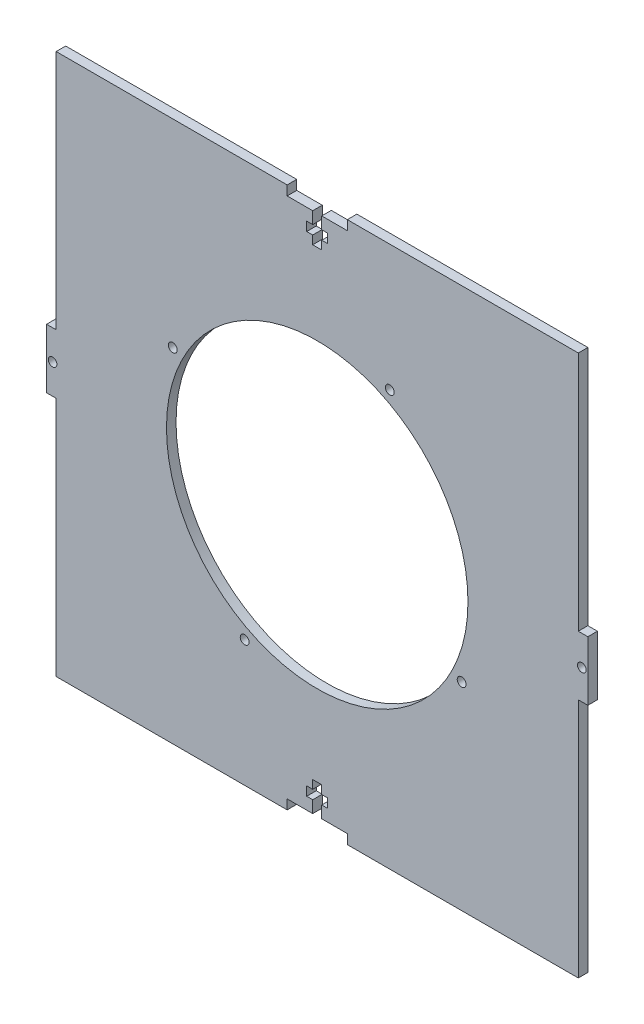
SolidWorks part; units mm, degrees
ref_plane "Front Plane" through (0, 0, 0) normal (0, 0, 1) x (1, 0, 0)
ref_plane "Top Plane" through (0, 0, 0) normal (0, 1, 0) x (1, 0, 0)
ref_plane "Right Plane" through (0, 0, 0) normal (1, 0, 0) x (0, 0, -1)
sketch "Sketch3" plane through (0, 0, 0) normal (0, 0, 1) x (1, 0, 0)
  line L0 (-90, 0) -> (90, 0) construction
  line L1 (-90, 90) -> (90, 90)
  line L2 (-90, 90) -> (-90, -90)
  line L3 (-90, -90) -> (90, -90)
  line L4 (90, 90) -> (90, -90)
  line L5 (-90, 0) -> (42.6717, 0) construction
  line L6 (0, 90) -> (0, -90) construction
  line L7 (50.1292, 0) -> (50.1292, -50.1292) construction
  line L8 (50.1292, -50.1292) -> (-50.1292, -50.1292) construction
  line L9 (-50.1292, -50.1292) -> (-50.1292, 50.1292) construction
  line L10 (-50.1292, 50.1292) -> (50.1292, 50.1292) construction
  line L11 (50.1292, 50.1292) -> (50.1292, 0) construction
  circle A0 centre (0, 0) radius 50.1292
  circle A1 centre (-48.0294, 24.1296) radius 1.47
  circle A2 centre (-24.1296, -48.0294) radius 1.47
  circle A3 centre (48.0294, -24.1296) radius 1.47
  circle A4 centre (24.1296, 48.0294) radius 1.47
  dimension "D1" = 180
  dimension "D3" = 180
extrude "Boss-Extrude1" add sketch "Sketch3" along normal blind 3.18
sketch "Sketch4" plane through (0, 0, 3.18) normal (0, 0, 1) x (1, 0, 0)
  line L0 (-90, 90) -> (-90, -90) construction
  line L1 (90, -90) -> (90, 90) construction
  line L2 (-90, 0) -> (90, 0) construction
  line L3 (0.9399, -90) -> (0, -90) construction
  line L4 (90, 90) -> (-90, 90) construction
  line L5 (0, -90) -> (0, 90) construction
  line L6 (1.5, 86.82) -> (10, 86.82)
  line L7 (-10, 90) -> (10, 90)
  line L8 (-10, 90) -> (-10, 86.82)
  line L9 (-10, 86.82) -> (-1.5, 86.82)
  line L10 (10, 90) -> (10, 86.82)
  line L11 (-3.5, 82.82) -> (-1.5, 82.82)
  line L12 (-3.5, 82.82) -> (-3.5, 79.82)
  line L13 (-3.5, 79.82) -> (-1.5, 79.82)
  line L14 (3.5, 82.82) -> (3.5, 79.82)
  line L15 (1.5, 82.82) -> (3.5, 82.82)
  line L16 (-1.5, 86.82) -> (-1.5, 82.82)
  line L17 (-1.5, 77) -> (1.5, 77)
  line L18 (1.5, 86.82) -> (1.5, 82.82)
  line L19 (-90, -90) -> (90, -90) construction
  line L20 (1.5, 79.82) -> (3.5, 79.82)
  line L21 (-1.5, 79.82) -> (-1.5, 77)
  line L22 (1.5, 79.82) -> (1.5, 77)
  line L23 (1.5, -79.82) -> (1.5, -77)
  line L24 (-1.5, -79.82) -> (-1.5, -77)
  line L25 (1.5, -79.82) -> (3.5, -79.82)
  line L26 (1.5, -86.82) -> (1.5, -82.82)
  line L27 (-1.5, -77) -> (1.5, -77)
  line L28 (-1.5, -86.82) -> (-1.5, -82.82)
  line L29 (1.5, -82.82) -> (3.5, -82.82)
  line L30 (3.5, -82.82) -> (3.5, -79.82)
  line L31 (-3.5, -79.82) -> (-1.5, -79.82)
  line L32 (-3.5, -82.82) -> (-3.5, -79.82)
  line L33 (-3.5, -82.82) -> (-1.5, -82.82)
  line L34 (10, -90) -> (10, -86.82)
  line L35 (-10, -86.82) -> (-1.5, -86.82)
  line L36 (-10, -90) -> (-10, -86.82)
  line L37 (-10, -90) -> (10, -90)
  line L38 (1.5, -86.82) -> (10, -86.82)
  dimension "D1" = 20
  dimension "D2" = 3.18
  dimension "D3" = 4
  dimension "D4" = 3
  dimension "D5" = 3
  dimension "D6" = 13
  dimension "D7" = 7
sketch "Sketch5" plane through (0, 0, 3.18) normal (0, 0, 1) x (1, 0, 0)
  line L0 (-90, 0) -> (90, 0) construction
  line L1 (-90, 90) -> (-86.82, 90)
  line L2 (-90, 90) -> (-90, 9.875)
  line L3 (-90, 9.875) -> (-86.82, 9.875)
  line L4 (-86.82, 90) -> (-86.82, 9.875)
  line L5 (-90, -90) -> (-86.82, -90)
  line L6 (-90, -90) -> (-90, -9.875)
  line L7 (-90, -9.875) -> (-86.82, -9.875)
  line L8 (-86.82, -90) -> (-86.82, -9.875)
  line L9 (-90, 90) -> (-90, -90) construction
  line L10 (0, 90) -> (0, -90) construction
  line L11 (86.82, -90) -> (86.82, -9.875)
  line L12 (90, -9.875) -> (86.82, -9.875)
  line L13 (90, -90) -> (90, -9.875)
  line L14 (90, -90) -> (86.82, -90)
  line L15 (86.82, 90) -> (86.82, 9.875)
  line L16 (90, 9.875) -> (86.82, 9.875)
  line L17 (90, 90) -> (90, 9.875)
  line L18 (90, 90) -> (86.82, 90)
  circle A0 centre (-88, 0) radius 1.436
  circle A1 centre (88, 0) radius 1.436
  dimension "D4" = 2.872
  dimension "D5" = 2
  dimension "D1" = 3.18
  dimension "D2" = 3.18
  dimension "D3" = 19.75
extrude "Cut-Extrude1" cut sketch "Sketch4" against normal through all
extrude "Cut-Extrude2" cut sketch "Sketch5" against normal through all
